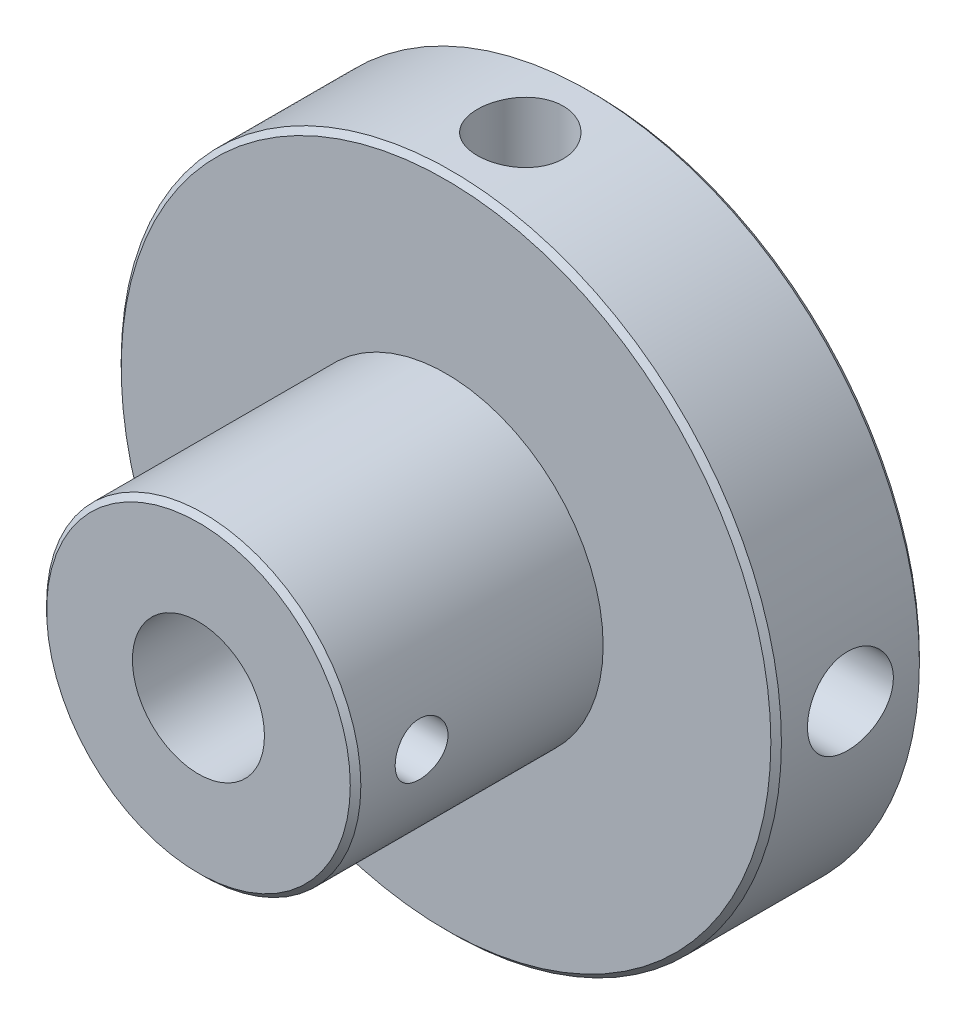
SolidWorks part; units mm, degrees
ref_plane "Front" through (0, 0, 0) normal (0, 0, 1) x (1, 0, 0)
ref_plane "Top" through (0, 0, 0) normal (0, 1, 0) x (1, 0, 0)
ref_plane "Right" through (0, 0, 0) normal (1, 0, 0) x (0, 0, -1)
sketch "Sketch1" plane through (0, 0, 0) normal (0, 0, 1) x (1, 0, 0)
  circle A0 centre (0, 0) radius 31.75
extrude "Base-Extrude" add sketch "Sketch1" along normal blind 14.2875
sketch "Sketch2" plane through (0, 0, 0) normal (0, 0, 1) x (1, 0, 0)
  circle A0 centre (0, 0) radius 15.113
  dimension "D1" = 30.226
extrude "Boss-Extrude1" add sketch "Sketch2" along normal blind 38.1
sketch "Sketch3" plane through (0, 0, 0) normal (0, 0, 1) x (1, 0, 0)
  circle A0 centre (0, 0) radius 6.35
  dimension "D1" = 12.7
extrude "Cut-Extrude1" cut sketch "Sketch3" along normal blind 77.724
ref_plane "Plane1" through (0, 0, 38.1) normal (0, 0, 1) x (1, 0, 0)
sketch "Sketch4" plane through (0, 0, 38.1) normal (0, 0, 1) x (1, 0, 0)
  circle A0 centre (0, 0) radius 6.35
  dimension "D1" = 12.7
extrude "Cut-Extrude2" [suppressed] cut sketch "Sketch4" against normal blind 15.24
ref_plane "Plane2" through (38.3366, 0, 0) normal (1, 0, 0) x (0, 0, -1)
sketch "Sketch5" plane through (38.3366, 0, 0) normal (1, 0, 0) x (0, 0, -1)
  line L0 (-37.7311, 0) -> (7.0252, 0) construction
  line L1 (-38.1, 0) -> (0, 0) construction
  line L2 (-30.5881, 20.9527) -> (-30.5881, -24.6861) construction
  line L3 (-38.1, 15.113) -> (-38.1, -15.113) construction
  line L4 (-30.588, 116.1504) -> (-30.588, -12.0977) construction
  line L5 (-30.588, 52.1147) -> (-30.588, 53.2632) construction
  circle A0 centre (-31.75, 0) radius 2.54
  dimension "D1" = 5.08
  dimension "D3" = 6.35
  dimension "D2" = 0.0001
extrude "Cut-Extrude3" cut sketch "Sketch5" against normal blind 37.846
cosmetic thread "Cosmetic Thread1" parameters "D1"=9.2931, "D2"=6.35
sketch "Sketch6" plane through (38.3366, 0, 0) normal (1, 0, 0) x (0, 0, -1)
  line L0 (-7.1437, 31.75) -> (-7.1437, -24.1514) construction
  line L1 (0, 31.75) -> (-14.2875, 31.75) construction
  line L2 (0, 0) -> (-20.6765, 0) construction
  line L3 (-38.1, 0) -> (0, 0) construction
  circle A0 centre (-7.1437, 0) radius 4.1275
  dimension "D1" = 8.255
extrude "Cut-Extrude4" cut sketch "Sketch6" against normal blind 25.8572
ref_plane "Plane3" through (0, 27.7002, 0) normal (0, 1, 0) x (-1, 0, 0)
sketch "Sketch7" plane through (0, 27.7002, 0) normal (0, 1, 0) x (-1, 0, 0)
  line L0 (25.1921, 7.1437) -> (-30.2011, 7.1437) construction
  line L1 (-12.4794, 7.1437) -> (-31.75, 7.1437) construction
  line L2 (0, 0) -> (0, 41.127) construction
  line L3 (0, 38.1) -> (0, 0) construction
  circle A0 centre (0, 7.1437) radius 4.1275
  dimension "D1" = 8.255
extrude "Cut-Extrude5" cut sketch "Sketch7" against normal blind 15.24
mirror "Mirror1" about plane through (0, 0, 0) normal (1, 0, 0) of "Cut-Extrude4"
mirror "Mirror2" about plane through (0, 0, 0) normal (0, 1, 0) of "Cut-Extrude5"
sketch "Sketch8" plane through (0, 27.7002, 0) normal (0, 1, 0) x (-1, 0, 0)
  circle A0 centre (0, 7.1437) radius 4.1275
extrude "Cut-Extrude6" cut sketch "Sketch8" along normal blind 26.51
ref_plane "Plane4" through (0, -34.1281, 0) normal (0, 1, 0) x (-1, 0, 0)
sketch "Sketch9" plane through (0, -34.1281, 0) normal (0, 1, 0) x (-1, 0, 0)
  circle A0 centre (0, 7.1437) radius 4.1275
extrude "Cut-Extrude7" cut sketch "Sketch9" along normal blind 10.508
chamfer "Chamfer1" distance 0.508 angle 45 4 edges at (31.75, 0, 0) (31.75, 0, 14.2875) (6.35, 0, 0) (15.113, 0, 38.1)
